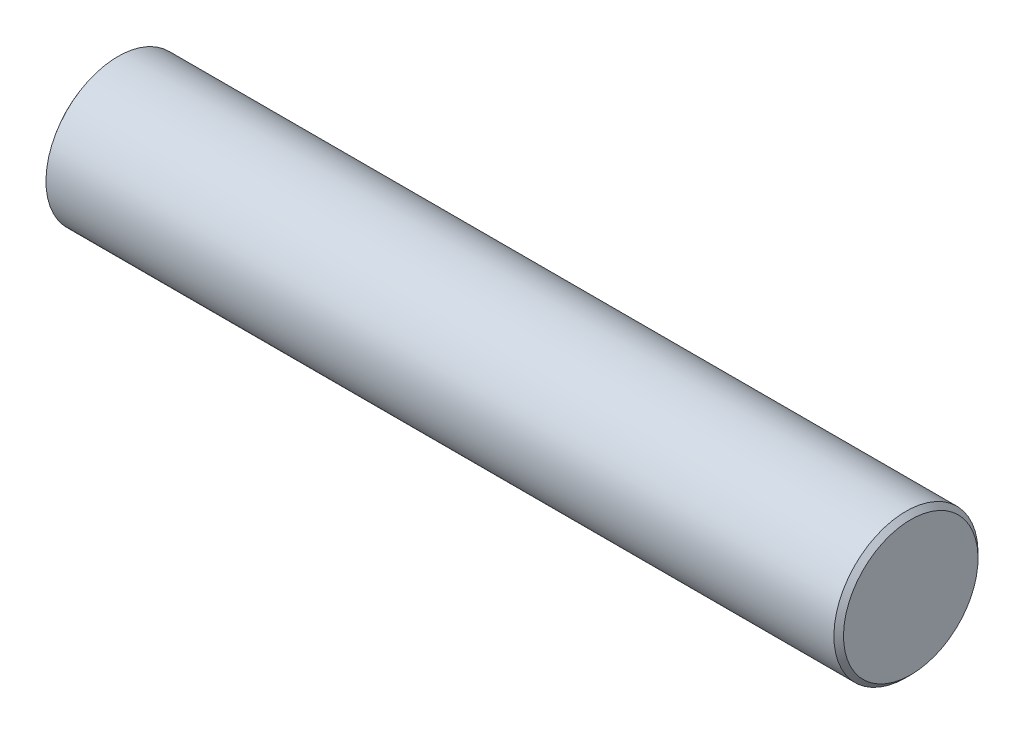
SolidWorks part; units mm, degrees
material "1.4305 (X8CrNiS18-9)"
ref_plane "Vorne" through (0, 0, 0) normal (0, 0, 1) x (1, 0, 0)
ref_plane "Oben" through (0, 0, 0) normal (0, 1, 0) x (1, 0, 0)
ref_plane "Rechts" through (0, 0, 0) normal (1, 0, 0) x (0, 0, -1)
sketch "Skizze12" plane through (0, 0, 0) normal (0, 0, 1) x (1, 0, 0)
  line L0 (-83, 0) -> (83, 0) construction
  line L1 (-83, 0) -> (-83, 13.6214)
  line L3 (83, 14) -> (83, 0)
  line L4 (82, 15) -> (83, 14)
  line L5 (-83, 13.6214) -> (-82, 15)
  line L6 (-83, 0) -> (83, 0)
  line L7 (-83, 0) -> (-107.4093, 0) construction
  line L9 (-82, 15) -> (82, 15)
  point P4 (-82.9244, 14.6186)
  point P5 (83, 15)
  point P6 (0, 0)
  point P10 (0, 15)
  dimension "D1" = 30
  dimension "D2" = 166
revolve "Rotation1" add sketch "Skizze12" angle 360 about L0
